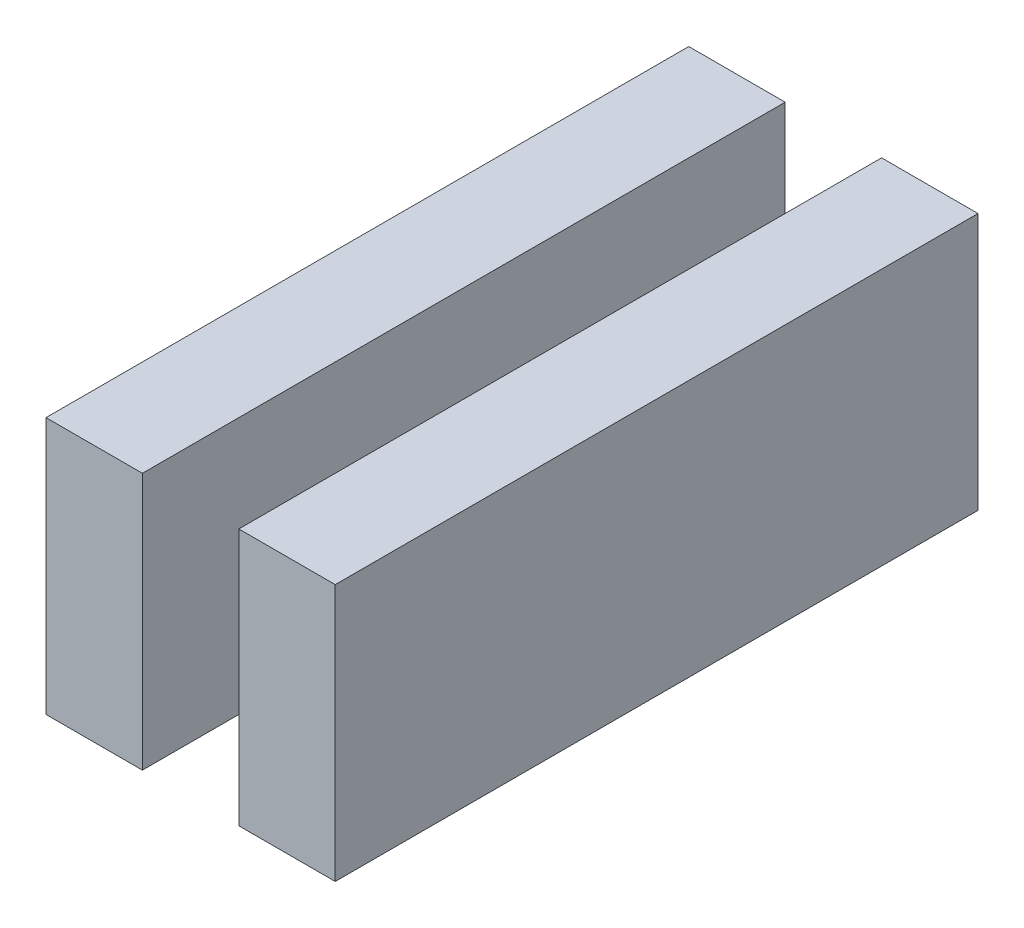
SolidWorks part; units mm, degrees
ref_plane "前视基准面" through (0, 0, 0) normal (0, 0, 1) x (1, 0, 0)
ref_plane "上视基准面" through (0, 0, 0) normal (0, 1, 0) x (1, 0, 0)
ref_plane "右视基准面" through (0, 0, 0) normal (1, 0, 0) x (0, 0, -1)
sketch "Model" plane through (0, 0, 0) normal (0, 0, 1) x (1, 0, 0)
  line L3 (47.75, 94.5) -> (47.75, 90.5)
  line L4 (47.75, 90.5) -> (46.25, 90.5)
  line L5 (47.75, 94.5) -> (46.25, 94.5)
  line L6 (49.25, 94.5) -> (49.25, 90.5)
  line L7 (49.25, 90.5) -> (50.75, 90.5)
  line L8 (49.25, 94.5) -> (50.75, 94.5)
  line L26 (46.25, 94.5) -> (46.25, 90.5)
  line L27 (50.75, 94.5) -> (50.75, 90.5)
  dimension "D1" = 4
  dimension "D2" = 1.5
  dimension "D3" = 1.5
  dimension "D4" = 4
  dimension "D5" = 1.5
extrude "凸台-拉伸1" add sketch "Model" along normal blind 10 contours L27 L8 L6 L7 | L3 L4 L26 L5
